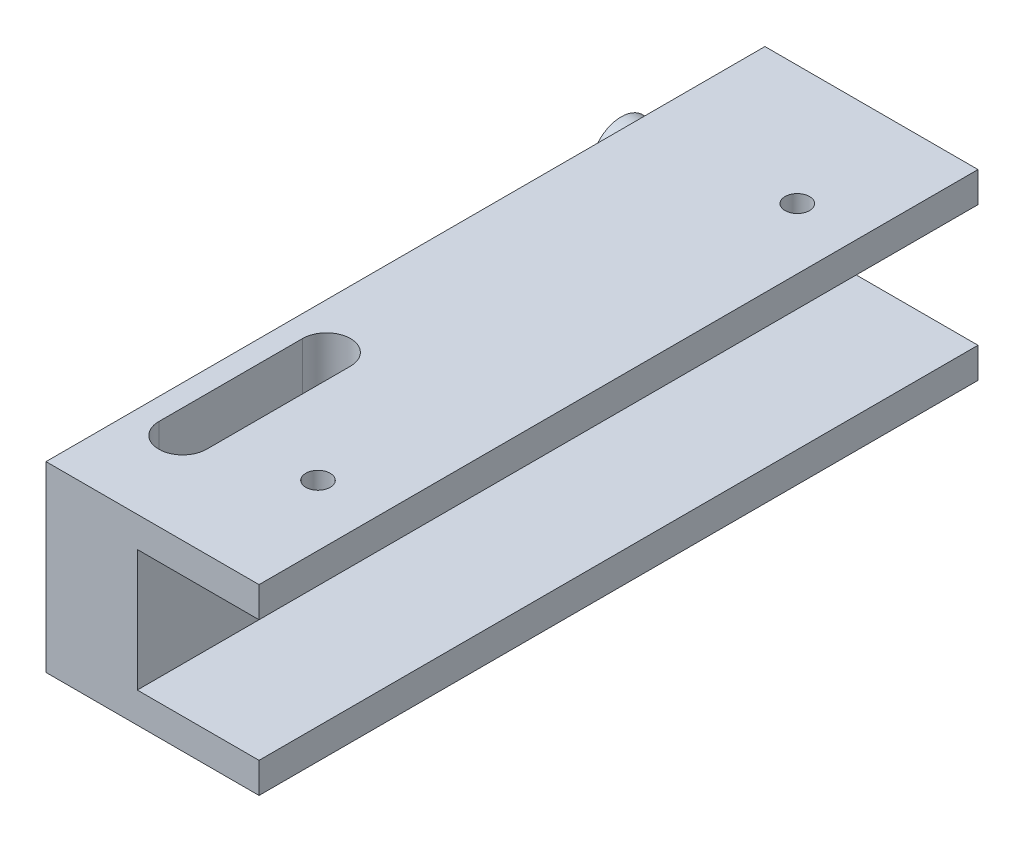
SolidWorks part; units mm, degrees
ref_plane "Alzado" through (0, 0, 0) normal (0, 0, 1) x (1, 0, 0)
ref_plane "Planta" through (0, 0, 0) normal (0, 1, 0) x (1, 0, 0)
ref_plane "Vista lateral" through (0, 0, 0) normal (1, 0, 0) x (0, 0, -1)
sketch "Croquis1" plane through (0, 0, 0) normal (0, 0, 1) x (1, 0, 0)
  line L0 (0, 12.7) -> (0, -12.7)
  line L1 (0, -12.7) -> (25.4, -12.7)
  line L2 (0, 12.7) -> (25.4, 12.7)
  line L3 (-19.05, 19.05) -> (-19.05, -19.05)
  line L4 (-19.05, -19.05) -> (25.4, -19.05)
  line L5 (25.4, 12.7) -> (25.4, 19.05)
  line L6 (25.4, -19.05) -> (25.4, -12.7)
  line L7 (-19.05, 19.05) -> (25.4, 19.05)
  point P5 (0, 0)
  point P11 (-19.05, 0)
  dimension "D1" = 25.4
  dimension "D2" = 25.4
  dimension "D3" = 38.1
  dimension "D4" = 44.45
extrude "Saliente-Extruir1" add sketch "Croquis1" along normal mid plane 150
sketch "Croquis2" plane through (-19.05, 0, 0) normal (-1, 0, 0) x (0, 0, 1)
  circle A0 centre (-60, 0) radius 6.35
  dimension "D1" = 12.7
  dimension "D2" = 60
extrude "Saliente-Extruir2" add sketch "Croquis2" along normal blind 15
sketch "Croquis3" plane through (0, 0, 0) normal (0, 1, 0) x (1, 0, 0)
  line L0 (-9.525, -26) -> (-9.525, -56) construction
  line L1 (-4.525, -26) -> (-4.525, -56)
  line L2 (-14.525, -26) -> (-14.525, -56)
  line L3 (0, -11.2567) -> (-19.05, -11.2567) construction
  line L4 (0, -75) -> (0, 75) construction
  line L5 (-19.05, -75) -> (-19.05, 75) construction
  line L6 (25.4, -75) -> (-19.05, -75) construction
  arc A0 (-4.525, -26) -> (-14.525, -26) centre (-9.525, -26) ccw
  arc A1 (-14.525, -56) -> (-4.525, -56) centre (-9.525, -56) ccw
  point P2 (-9.525, -41)
  point P7 (-9.525, -11.2567)
  point P18 (-9.525, -42.5)
  dimension "D1" = 10
  dimension "D2" = 30
  dimension "D3" = 34
extrude "Cortar-Extruir1" cut sketch "Croquis3" against normal through all both and the other way through all
sketch "Croquis4" plane through (0, 0, 0) normal (1, 0, 0) x (0, 0, -1)
  arc A0 (-14.7146, -6.5367) -> (-14.7146, 6.5367) centre (60, 0) cw construction
  arc A1 (-18.2013, 6.8417) -> (-18.2013, -6.8417) centre (60, 0) ccw
  arc A2 (-11.2279, 6.2316) -> (-11.2279, -6.2316) centre (60, 0) ccw
  arc A3 (-11.2279, 6.2316) -> (-18.2013, 6.8417) centre (-14.7146, 6.5367) ccw
  arc A4 (-18.2013, -6.8417) -> (-11.2279, -6.2316) centre (-14.7146, -6.5367) ccw
  circle A5 centre (60, 0) radius 6.35 construction
  point P3 (-15, 0)
  point P8 (10, 0)
  point P9 (0, 0)
  point P13 (-13.091, 0)
  point P14 (-10.3693, 0)
  point P15 (-6.5891, 0)
  point P16 (-18.5206, 0)
  dimension "D1" = 7
  dimension "D2" = 75
  dimension "D3" = 10
extrude "Cortar-Extruir2" cut sketch "Croquis4" against normal through all both and the other way through all
hole_wizard "Taladro roscado 1/4-201" positions "Croquis5" profile "Croquis6" tap size "1/4-20" standard "Ansi Inch"
sketch "Croquis5" plane through (0, 19.05, 0) normal (0, 1, 0) x (1, 0, 0)
  line L0 (0, 0) -> (-50000, 0) construction
  line L2 (0, 75) -> (25.4, 75) construction
  point P0 (12.7, -50)
  point P2 (12.7, 50)
  point P10 (0, 0)
  point P11 (0, 0)
  point P14 (12.7, 75)
  point P15 (0, 0)
  dimension "D1" = 50
sketch "Croquis6" plane through (12.7, 19.05, 50) normal (1, 0, 0) x (0, 0, 1)
  line L0 (0, 0) -> (0, 6.35)
  line L1 (0, 6.35) -> (2.5527, 6.35)
  line L2 (2.5527, 6.35) -> (2.5527, 0)
  line L5 (2.5527, 0) -> (0, 0)
  line L11 (0, -6.35) -> (0, 107.95) construction
  dimension "Diámetro de perforador para roscar hasta el siguiente" = 5.1054
  dimension "Profundidad de perforador para roscar hasta el siguiente" = 6.35
cosmetic thread "Rosca de taladro1" parameters "D2"=6.35
cosmetic thread "Rosca de taladro2" parameters "D2"=6.35
